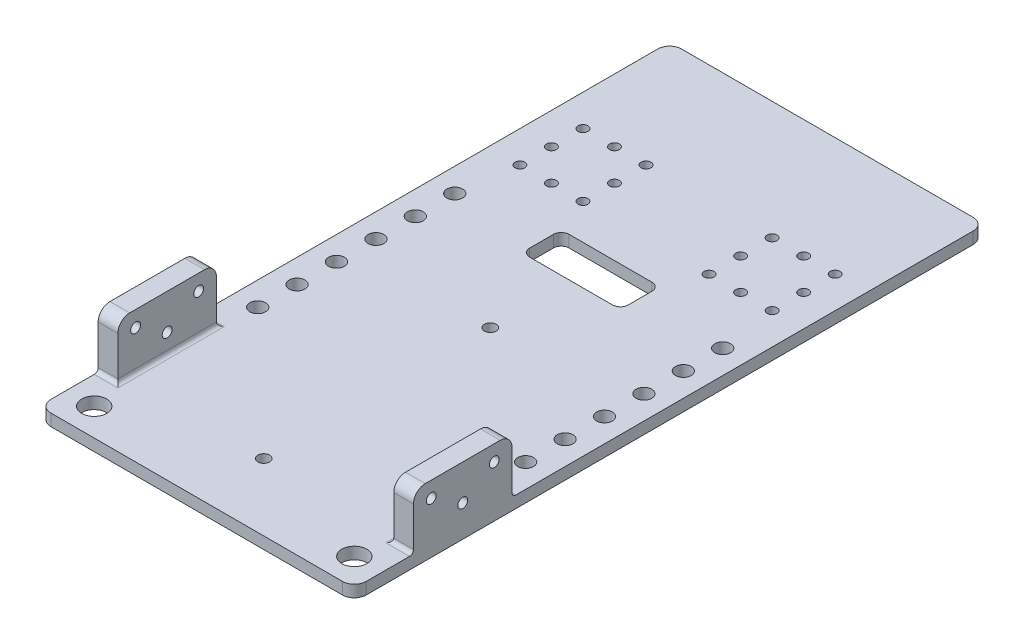
SolidWorks part; units mm, degrees
ref_plane "Front" through (0, 0, 0) normal (0, 0, 1) x (1, 0, 0)
ref_plane "Top" through (0, 0, 0) normal (0, 1, 0) x (1, 0, 0)
ref_plane "Right" through (0, 0, 0) normal (1, 0, 0) x (0, 0, -1)
sketch "Sketch1" plane through (0, 0, 0) normal (0, 1, 0) x (1, 0, 0)
  line L0 (8, 130) -> (16, 130) construction
  line L1 (0, 0) -> (80, 0)
  line L2 (0, 0) -> (0, 160)
  line L3 (0, 160) -> (80, 160)
  line L4 (80, 0) -> (80, 160)
  line L5 (16, 130) -> (24, 130) construction
  line L6 (24, 130) -> (24, 122) construction
  line L7 (24, 122) -> (24, 114) construction
  line L8 (24, 114) -> (16, 114) construction
  line L9 (16, 114) -> (8, 114) construction
  line L10 (8, 114) -> (8, 122) construction
  line L11 (8, 122) -> (8, 130) construction
  line L12 (8, 122) -> (24, 122) construction
  line L13 (16, 130) -> (16, 114) construction
  line L14 (40, 160) -> (40, 0) construction
  line L15 (40, 105) -> (40, 160) construction
  line L16 (52.5, 105) -> (27.5, 105)
  line L17 (52.5, 105) -> (52.5, 95)
  line L18 (52.5, 95) -> (27.5, 95)
  line L19 (27.5, 105) -> (27.5, 95)
  circle A0 centre (8, 130) radius 1.25
  circle A1 centre (16, 130) radius 1.25
  circle A2 centre (24, 130) radius 1.25
  circle A3 centre (24, 122) radius 1.25
  circle A4 centre (24, 114) radius 1.25
  circle A5 centre (16, 114) radius 1.25
  circle A6 centre (8, 114) radius 1.25
  circle A7 centre (8, 122) radius 1.25
  circle A8 centre (72, 130) radius 1.25
  circle A9 centre (72, 122) radius 1.25
  circle A10 centre (72, 114) radius 1.25
  circle A11 centre (64, 114) radius 1.25
  circle A12 centre (64, 130) radius 1.25
  circle A13 centre (56, 130) radius 1.25
  circle A14 centre (56, 122) radius 1.25
  circle A15 centre (56, 114) radius 1.25
  circle A16 centre (40, 17) radius 1.5
  circle A17 centre (40, 74.5) radius 1.5
  circle A18 centre (7, 7) radius 3.175
  circle A19 centre (73, 7) radius 3.175
  dimension "D3" = 2.5
  dimension "D10" = 3
  dimension "D11" = 57.5
  dimension "D12" = 17
  dimension "D13" = 6.35
  dimension "D1" = 80
  dimension "D2" = 160
  dimension "D4" = 8
  dimension "D5" = 8
  dimension "D6" = 8
  dimension "D7" = 8
  dimension "D8" = 8
  dimension "D9" = 30
  dimension "D14" = 7
  dimension "D15" = 7
  dimension "D16" = 55
  dimension "D17" = 25
  dimension "D18" = 10
extrude "Boss-Extrude1" add sketch "Sketch1" along normal blind 3
sketch "Sketch2" plane through (0, 3, 0) normal (0, 1, 0) x (1, 0, 0)
  line L0 (0, 160) -> (0, 0) construction
  line L1 (0, 15) -> (5, 15)
  line L2 (0, 15) -> (0, 40)
  line L3 (0, 40) -> (5, 40)
  line L4 (5, 15) -> (5, 40)
  line L5 (40, 0) -> (40, 52.904) construction
  line L6 (0, 0) -> (80, 0) construction
  line L7 (75, 15) -> (75, 40)
  line L8 (80, 40) -> (75, 40)
  line L9 (80, 15) -> (80, 40)
  line L10 (80, 15) -> (75, 15)
  dimension "D1" = 15
  dimension "D2" = 25
  dimension "D3" = 5
extrude "Boss-Extrude2" add sketch "Sketch2" along normal blind 14
fillet "Fillet1" radius 1 6 edges at (77.5, 3, -15) (75, 3, -27.5) (77.5, 3, -40) (5, 3, -27.5)
fillet "Fillet2" radius 3 4 edges at (0, 1.5, -160) (80, 1.5, -160) (80, 1.5, 0) (0, 1.5, 0)
fillet "Fillet3" radius 3 4 edges at (77.5, 17, -40) (77.5, 17, -15) (2.5, 17, -15) (2.5, 17, -40)
sketch "Sketch4" plane through (0, 0, 0) normal (-1, 0, 0) x (0, 0, 1)
  line L0 (-27.5, 17) -> (-27.5, 2.9198) construction
  line L1 (-37, 17) -> (-18, 17) construction
  line L2 (-35.5, 13) -> (-19.5, 13) construction
  circle A0 centre (-27.5, 8) radius 1.25
  circle A1 centre (-35.5, 13) radius 1.25
  circle A2 centre (-19.5, 13) radius 1.25
  dimension "D1" = 2.5
  dimension "D2" = 8
  dimension "D4" = 4
  dimension "D3" = 5
extrude "Cut-Extrude1" cut sketch "Sketch4" against normal through all
sketch "Sketch6" plane through (0, 3, 0) normal (0, 1, 0) x (1, 0, 0)
  line L0 (40, 0) -> (40, 121.542) construction
  line L1 (3, 0) -> (77, 0) construction
  line L2 (0, 157) -> (0, 41) construction
  circle A0 centre (6, 99.4674) radius 2
  circle A1 centre (74, 99.4674) radius 2
  dimension "D1" = 6
  dimension "D2" = 4
extrude "Cut-Extrude2" cut sketch "Sketch6" against normal blind 8.89
pattern_linear "LPattern1" count 6 spacing 10 along (0, 0, 1) of "Cut-Extrude2"
fillet "Fillet4" radius 2 4 edges at (52.5, 1.5, -95) (27.5, 1.5, -95) (27.5, 1.5, -105) (52.5, 1.5, -105)
